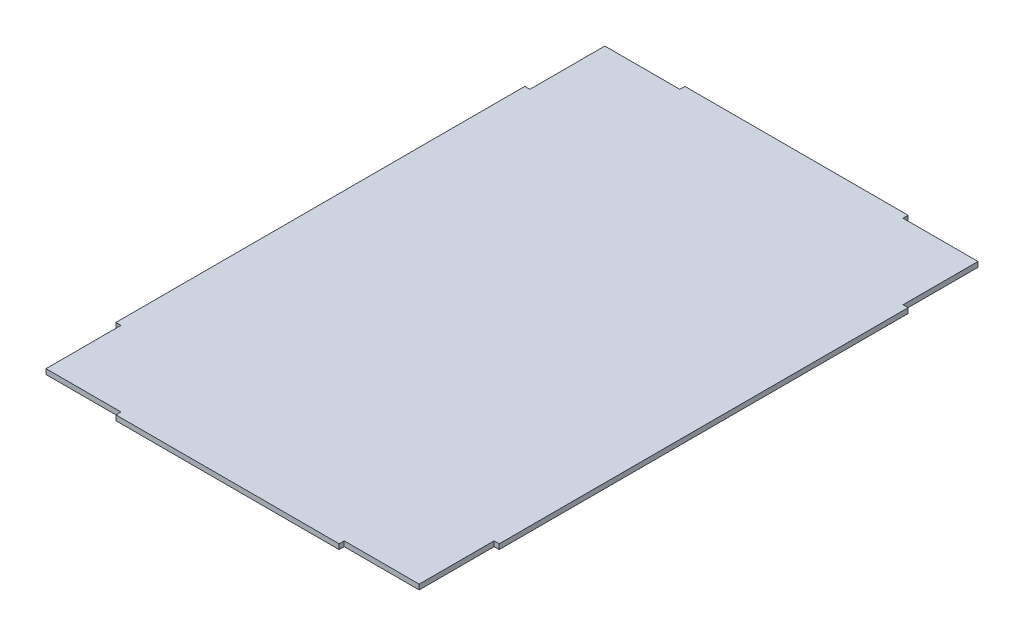
SolidWorks part; units mm, degrees
ref_plane "Front Plane" through (0, 0, 0) normal (0, 0, 1) x (1, 0, 0)
ref_plane "Top Plane" through (0, 0, 0) normal (0, 1, 0) x (1, 0, 0)
ref_plane "Right Plane" through (0, 0, 0) normal (1, 0, 0) x (0, 0, -1)
sketch "Sketch1" plane through (0, 0, 0) normal (0, 1, 0) x (1, 0, 0)
  line L7 (-239.5, -355.5) -> (239.5, -355.5)
  line L8 (-239.5, -355.5) -> (-239.5, 355.5)
  line L9 (-239.5, 355.5) -> (239.5, 355.5)
  line L10 (239.5, -355.5) -> (239.5, 355.5)
  point P0 (0, 0)
  point P1 (0, 0)
  point P2 (0, 0)
  point P3 (239.5, 0)
  point P6 (0, 0)
  point P11 (0, -355.5)
  dimension "D1" = 711
  dimension "D2" = 479
extrude "Boss-Extrude1" add sketch "Sketch1" along normal mid plane 6.35
sketch "Sketch2" plane through (0, 3.175, 0) normal (0, 1, 0) x (1, 0, 0)
  line L0 (-239.5, 355.5) -> (-239.5, 255.5)
  line L1 (-239.5, 355.5) -> (-239.5, -355.5) construction
  line L2 (-239.5, 255.5) -> (-233.15, 255.5)
  line L3 (-233.15, 255.5) -> (-233.15, 349.15)
  line L4 (-233.15, 349.15) -> (-139.5, 349.15)
  line L5 (-139.5, 349.15) -> (-139.5, 355.5)
  line L6 (239.5, 355.5) -> (-239.5, 355.5) construction
  line L7 (-139.5, 355.5) -> (-239.5, 355.5)
  line L8 (239.5, 355.5) -> (139.5, 355.5)
  line L9 (139.5, 355.5) -> (139.5, 349.15)
  line L10 (139.5, 349.15) -> (233.15, 349.15)
  line L11 (233.15, 349.15) -> (233.15, 255.5)
  line L12 (233.15, 255.5) -> (239.5, 255.5)
  line L13 (239.5, -355.5) -> (239.5, 355.5) construction
  line L14 (239.5, 255.5) -> (239.5, 355.5)
  line L15 (239.5, -355.5) -> (239.5, -255.5)
  line L16 (239.5, -255.5) -> (233.15, -255.5)
  line L17 (233.15, -255.5) -> (233.15, -349.15)
  line L18 (233.15, -349.15) -> (139.5, -349.15)
  line L19 (139.5, -349.15) -> (139.5, -355.5)
  line L20 (-239.5, -355.5) -> (239.5, -355.5) construction
  line L21 (139.5, -355.5) -> (239.5, -355.5)
  line L22 (-239.5, -355.5) -> (-139.5, -355.5)
  line L23 (-139.5, -355.5) -> (-139.5, -349.15)
  line L24 (-139.5, -349.15) -> (-233.15, -349.15)
  line L25 (-233.15, -349.15) -> (-233.15, -255.5)
  line L26 (-233.15, -255.5) -> (-239.5, -255.5)
  line L27 (-239.5, -255.5) -> (-239.5, -355.5)
  dimension "D1" = 100
  dimension "D2" = 6.35
extrude "Cut-Extrude1" cut sketch "Sketch2" against normal through all
